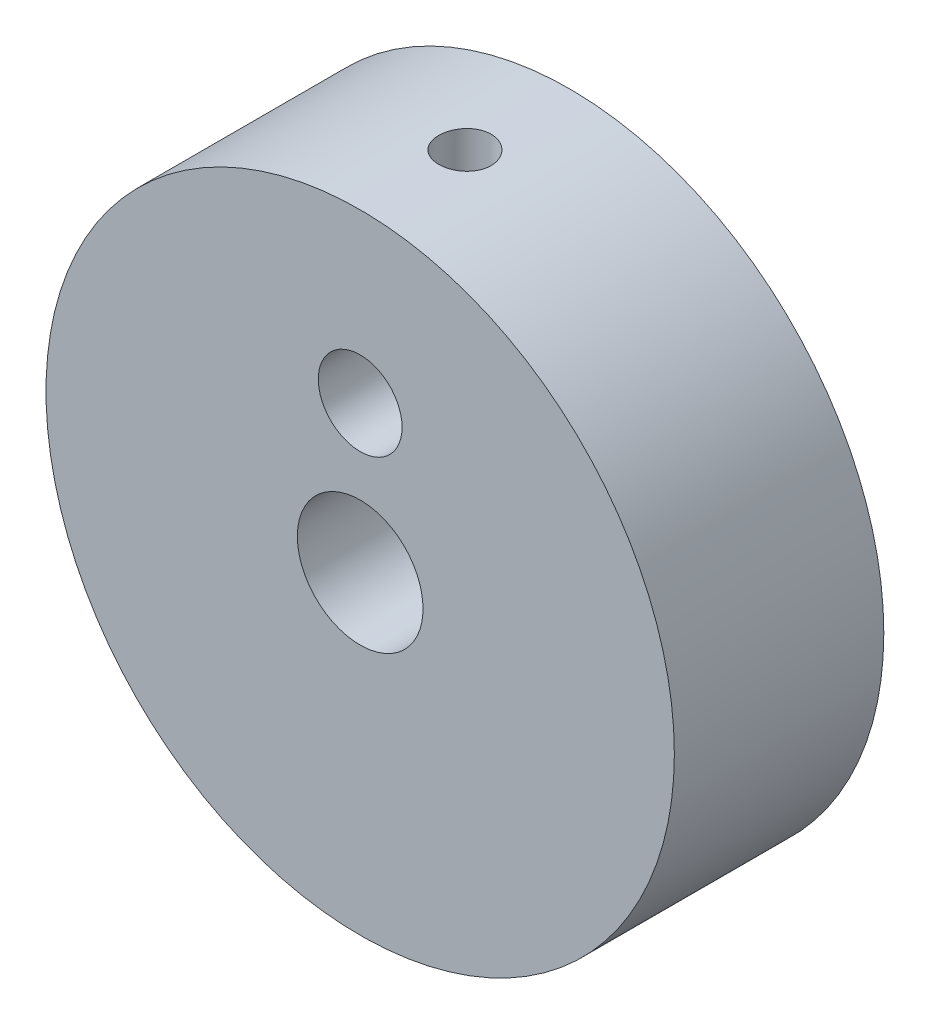
SolidWorks part; units mm, degrees
material "2024-T3"
ref_plane "正面" through (0, 0, 0) normal (0, 0, 1) x (1, 0, 0)
ref_plane "平面" through (0, 0, 0) normal (0, 1, 0) x (1, 0, 0)
ref_plane "右側面" through (0, 0, 0) normal (1, 0, 0) x (0, 0, -1)
sketch "ｽｹｯﾁ1" plane through (0, 0, 0) normal (0, 0, 1) x (1, 0, 0)
  circle A0 centre (0, 0) radius 15
  dimension "D1" = 30
extrude "ﾎﾞｽ - 押し出し1" add sketch "ｽｹｯﾁ1" along normal blind 10
sketch "ｽｹｯﾁ2" plane through (0, 0, 10) normal (0, 0, 1) x (1, 0, 0)
  line L0 (0, 0) -> (0, 7)
  circle A0 centre (0, 7) radius 2
  dimension "D2" = 4
  dimension "D1" = 7
  dimension "D3" = 7
sketch "ｽｹｯﾁ3" plane through (0, 0, 0) normal (0, 0, -1) x (-1, 0, 0)
  circle A0 centre (0, 0) radius 3
  dimension "D1" = 6
extrude "ｶｯﾄ - 押し出し1" cut sketch "ｽｹｯﾁ3" against normal through all contours A0
extrude "ｶｯﾄ - 押し出し2" cut sketch "ｽｹｯﾁ2" against normal through all contours A0
hole_wizard "M3x0.5 ねじ穴1" positions "3Dｽｹｯﾁ2" profile "ｽｹｯﾁ6" tap size "M3x0.5" standard "JIS"
sketch3d "3Dｽｹｯﾁ2"
  line L0 (0, 0, 0) -> (0, 7, 0)
  line L2 (0, 7, 0) -> (0, 15, 0)
  circle A0 centre (0, 0, 0) radius 3 construction
  circle A1 centre (0, 7, 0) radius 2 construction
  circle A2 centre (0, 0, 0) radius 3
  circle A3 centre (0, 7, 0) radius 2
  circle A4 centre (0, 0, 0) radius 15 construction
  point P0 (0, 15, 5)
  point P6 (0, 0, -3)
  point P9 (0, 7, 2)
  point P11 (0, 0, -3)
  point P13 (0, 7, 2)
  point P21 (0, 0, 15)
  dimension "D1" = 5
  dimension "D2" = 5
sketch "ｽｹｯﾁ6" plane through (0, 15, 5) normal (1, 0, 0) x (0, 0, 1)
  line L0 (0, 0) -> (0, 6)
  line L1 (0, 6) -> (1.25, 6)
  line L2 (1.25, 6) -> (1.25, 0)
  line L5 (1.25, 0) -> (0, 0)
  line L11 (0, -6.35) -> (0, 107.95) construction
  dimension "次ｻｰﾌｪｽまでのねじ下穴ﾄﾞﾘﾙ直径" = 2.5
  dimension "次ｻｰﾌｪｽまでのねじ下穴ﾄﾞﾘﾙの深さ" = 6
cosmetic thread "穴のねじ山1" parameters "D2"=3
hole_wizard "M3x0.5 ねじ穴2" positions "3Dｽｹｯﾁ3" profile "ｽｹｯﾁ7" tap size "M3x0.5" standard "JIS"
sketch3d "3Dｽｹｯﾁ3"
  line L0 (0, 0, 0) -> (0, 7, 0)
  line L2 (0, 0, 0) -> (0, -15, 0)
  circle A0 centre (0, 7, 0) radius 2 construction
  circle A1 centre (0, 0, 0) radius 3 construction
  circle A2 centre (0, 7, 0) radius 2
  circle A3 centre (0, 0, 0) radius 3
  circle A4 centre (0, 0, 0) radius 15 construction
  point P0 (0, -15, 5)
  point P5 (0, 7, 2)
  point P8 (0, 0, -3)
  point P10 (0, 7, 2)
  point P12 (0, 0, -3)
  point P20 (0, 0, 15)
  dimension "D1" = 5
  dimension "D2" = 5
sketch "ｽｹｯﾁ7" plane through (0, -15, 5) normal (1, 0, 0) x (0, 0, -1)
  line L0 (0, 0) -> (0, 12)
  line L1 (0, 12) -> (1.25, 12)
  line L2 (1.25, 12) -> (1.25, 0)
  line L5 (1.25, 0) -> (0, 0)
  line L11 (0, -6.35) -> (0, 107.95) construction
  dimension "次ｻｰﾌｪｽまでのねじ下穴ﾄﾞﾘﾙ直径" = 2.5
  dimension "次ｻｰﾌｪｽまでのねじ下穴ﾄﾞﾘﾙの深さ" = 12
cosmetic thread "穴のねじ山2" parameters "D2"=3
